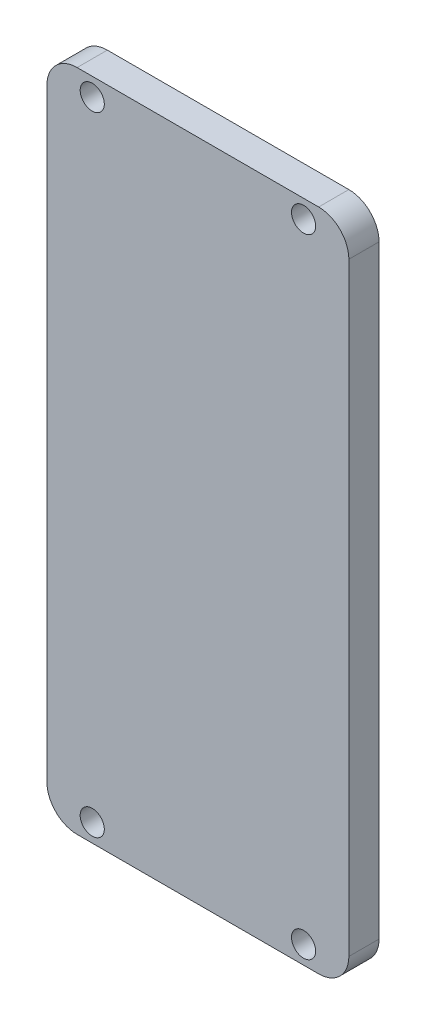
SolidWorks part; units mm, degrees
ref_plane "Ön Düzlem" through (0, 0, 0) normal (0, 0, 1) x (1, 0, 0)
ref_plane "Üst Düzlem" through (0, 0, 0) normal (0, 1, 0) x (1, 0, 0)
ref_plane "Sağ Düzlem" through (0, 0, 0) normal (1, 0, 0) x (0, 0, -1)
sketch "Çizim1" plane through (0, 0, 0) normal (0, 0, 1) x (1, 0, 0)
  line L0 (5, 0) -> (45, 0)
  line L1 (50, -5) -> (50, -105)
  line L2 (45, -110) -> (5, -110)
  line L3 (0, -105) -> (0, -5)
  arc A0 (5, -110) -> (0, -105) centre (5, -105) cw
  arc A1 (50, -105) -> (45, -110) centre (45, -105) cw
  arc A2 (45, 0) -> (50, -5) centre (45, -5) cw
  arc A3 (5, 0) -> (0, -5) centre (5, -5) ccw
  point P9 (50, -110)
  point P12 (50, 0)
  point P15 (0, 0)
  dimension "D3" = 5
  dimension "D1" = 50
  dimension "D2" = 110
extrude "Yükseklik-Ekstrüzyon1" add sketch "Çizim1" along normal blind 5
sketch "Çizim2" plane through (0, 0, 5) normal (0, 0, 1) x (1, 0, 0)
  line L0 (5, -110) -> (45, -110) construction
  line L1 (45, 0) -> (5, 0) construction
  line L2 (50, -105) -> (50, -5) construction
  line L3 (0, -5) -> (0, -105) construction
  circle A0 centre (7.5, -107) radius 2
  circle A1 centre (42.5, -107) radius 2
  circle A2 centre (7.5, -3) radius 2
  circle A3 centre (42.5, -3) radius 2
  dimension "D1" = 4
  dimension "D2" = 4
  dimension "D3" = 4
  dimension "D4" = 4
  dimension "D5" = 3
  dimension "D6" = 3
  dimension "D7" = 3
  dimension "D8" = 3
  dimension "D9" = 7.5
  dimension "D10" = 7.5
  dimension "D11" = 7.5
  dimension "D12" = 7.5
extrude "Kes-Ekstrüzyon1" cut sketch "Çizim2" against normal blind 5
